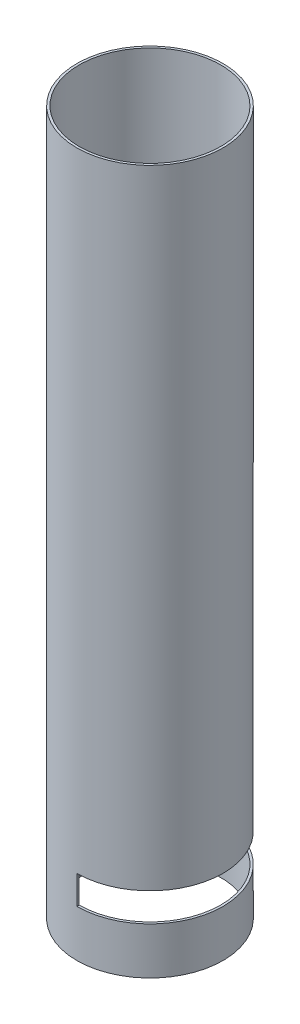
SolidWorks part; units mm, degrees
ref_plane "Front Plane" through (0, 0, 0) normal (0, 0, 1) x (1, 0, 0)
ref_plane "Top Plane" through (0, 0, 0) normal (0, 1, 0) x (1, 0, 0)
ref_plane "Right Plane" through (0, 0, 0) normal (1, 0, 0) x (0, 0, -1)
other "Default"
sketch "Sketch1" plane through (0, 0, 0) normal (0, 1, 0) x (1, 0, 0)
  circle A0 centre (0, 0) radius 30.1625
  circle A1 centre (0, 0) radius 31.165
  dimension "ID" = 60.325
  dimension "OD" = 62.33
extrude "Boss-Extrude1" add sketch "Sketch1" along normal mid plane 300
ref_plane "Plane1" through (0, -130, 0) normal (0, -1, 0) x (-1, 0, 0)
sketch "Sketch2" plane through (0, -130, 0) normal (0, -1, 0) x (-1, 0, 0)
  line L1 (0, 31.165) -> (-31.165, 31.165)
  line L2 (0, 31.165) -> (0, -31.165)
  line L3 (0, -31.165) -> (-31.165, -31.165)
  line L4 (-31.165, 31.165) -> (-31.165, -31.165)
  circle A1 centre (0, 0) radius 31.165 construction
  point P4 (0, 0)
  point P7 (0, 0)
extrude "Slot" cut sketch "Sketch2" against normal blind 12.2
